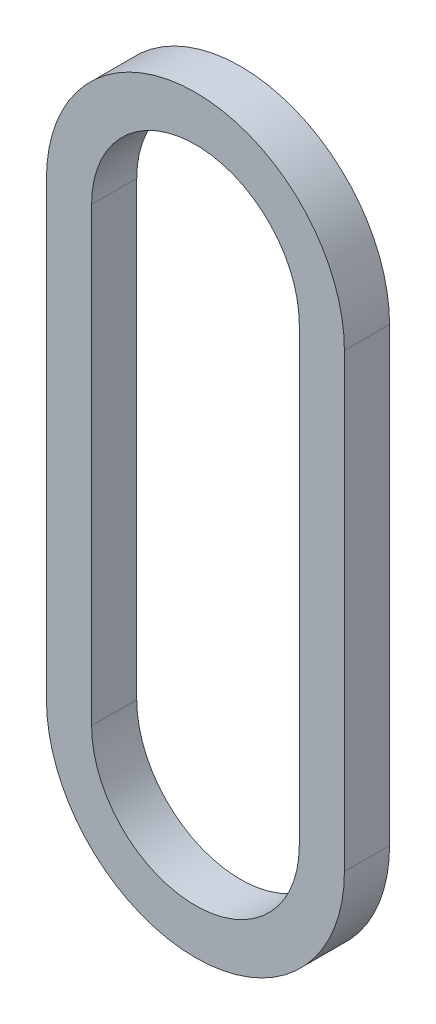
SolidWorks part; units mm, degrees
ref_plane "前视基准面" through (0, 0, 0) normal (0, 0, 1) x (1, 0, 0)
ref_plane "上视基准面" through (0, 0, 0) normal (0, 1, 0) x (1, 0, 0)
ref_plane "右视基准面" through (0, 0, 0) normal (1, 0, 0) x (0, 0, -1)
other "Configuration Table"
sketch "草图1" plane through (0, 0, 0) normal (0, 0, 1) x (1, 0, 0)
  line L0 (0, -50) -> (0, 50) construction
  line L1 (-23, -50) -> (-23, 50)
  line L2 (23, -50) -> (23, 50)
  line L3 (-33, -50) -> (-33, 50)
  line L4 (33, -50) -> (33, 50)
  arc A0 (-23, -50) -> (23, -50) centre (0, -50) ccw
  arc A1 (23, 50) -> (-23, 50) centre (0, 50) ccw
  arc A2 (33, 50) -> (-33, 50) centre (0, 50) ccw
  arc A3 (-33, -50) -> (33, -50) centre (0, -50) ccw
  point P2 (0, 0)
  dimension "D1" = 46
  dimension "D2" = 100
  dimension "D3" = 10
extrude "凸台-拉伸1" add sketch "草图1" along normal blind 10
